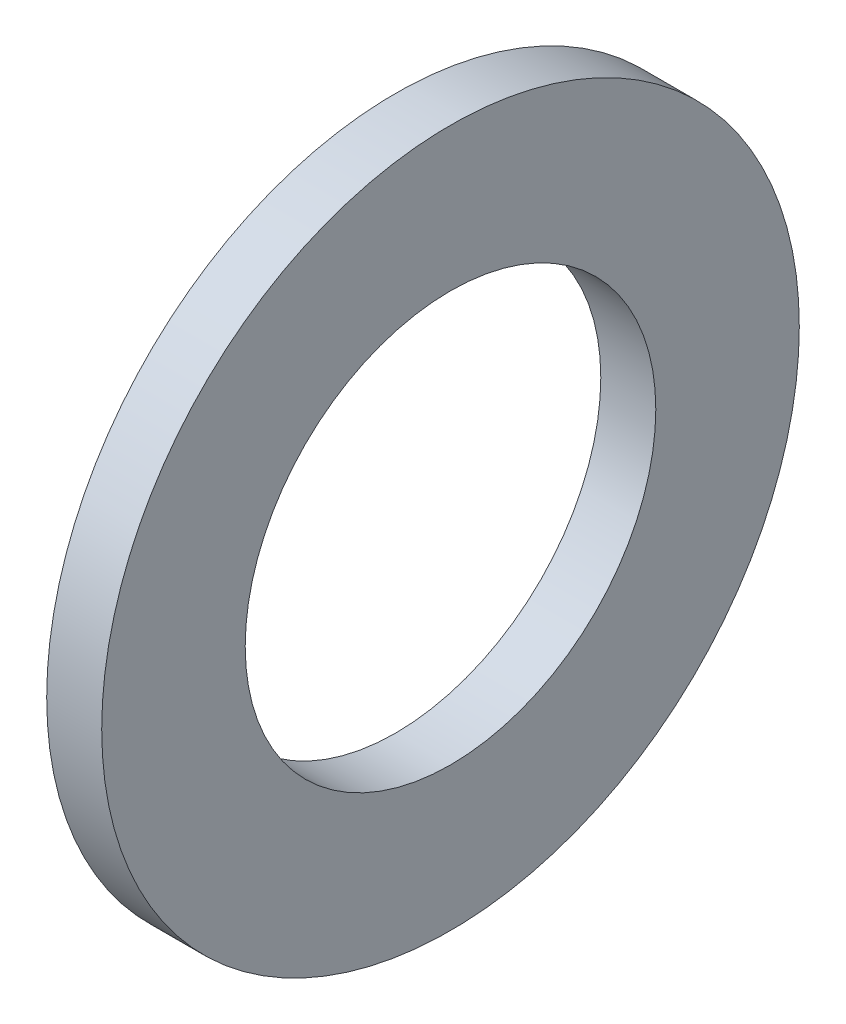
SolidWorks part; units mm, degrees
ref_plane "Front Plane" through (0, 0, 0) normal (0, 0, 1) x (1, 0, 0)
ref_plane "Top Plane" through (0, 0, 0) normal (0, 1, 0) x (1, 0, 0)
ref_plane "Right Plane" through (0, 0, 0) normal (1, 0, 0) x (0, 0, -1)
sketch "Sketch1" plane through (0, 0, 0) normal (1, 0, 0) x (0, 0, -1)
  circle A0 centre (0, 0) radius 11.1125
  circle A1 centre (0, 0) radius 6.5405
  dimension "OD" = 22.225
  dimension "ID" = 13.081
extrude "Boss-Extrude1" add sketch "Sketch1" along normal blind 1.7526
